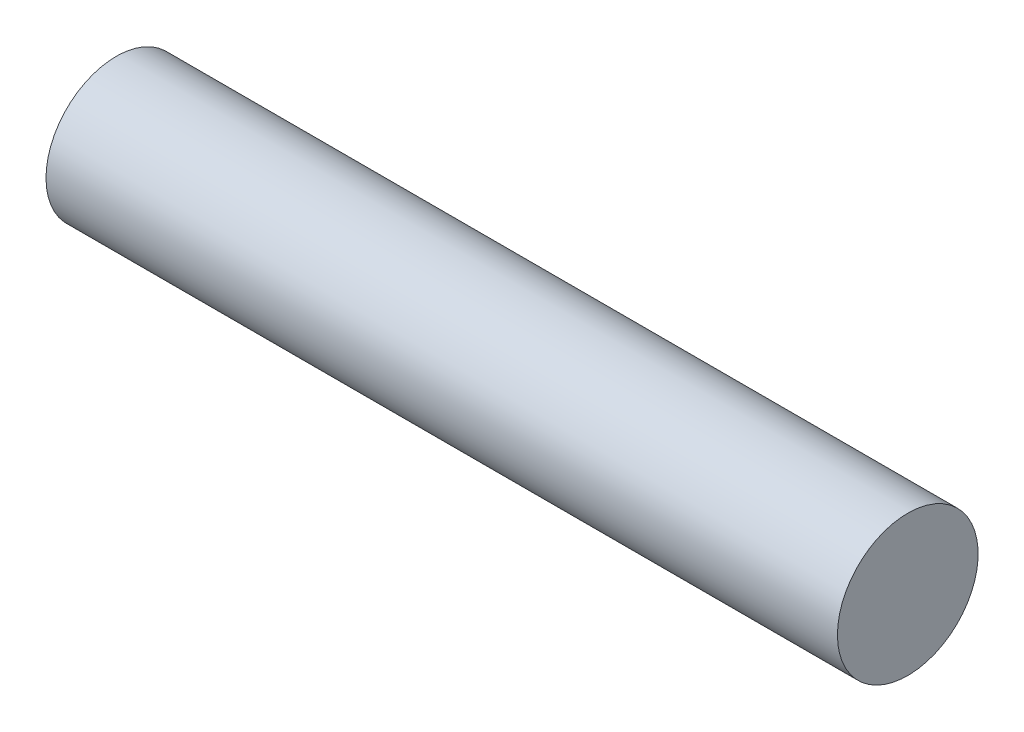
SolidWorks part; units mm, degrees
ref_plane "前视基准面" through (0, 0, 0) normal (0, 0, 1) x (1, 0, 0)
ref_plane "上视基准面" through (0, 0, 0) normal (0, 1, 0) x (1, 0, 0)
ref_plane "右视基准面" through (0, 0, 0) normal (1, 0, 0) x (0, 0, -1)
other "Configuration Table"
sketch "草图1" plane through (0, 0, 0) normal (0, 0, 1) x (1, 0, 0)
  line L0 (0, 0) -> (40.0305, 0) construction
  line L1 (0, 0) -> (0, 8)
  line L2 (0, 8) -> (90, 8)
  line L3 (90, 8) -> (90, 0)
  line L4 (0, 0) -> (90, 0)
  dimension "D1" = 8
  dimension "D2" = 90
revolve "旋转1" add sketch "草图1" angle 360 about L0
